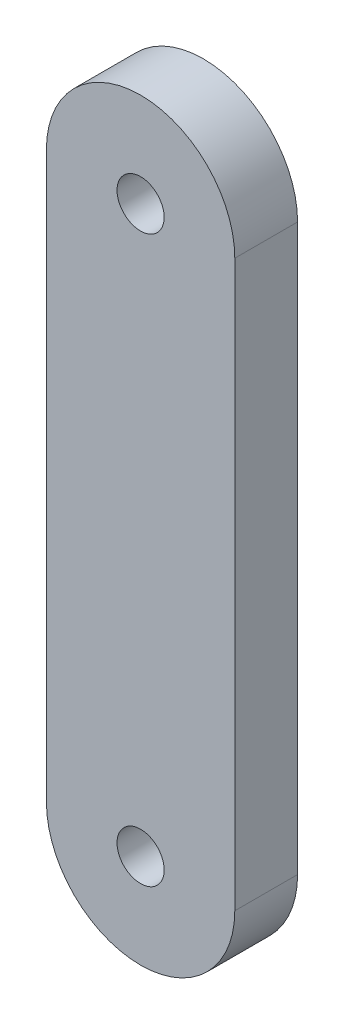
SolidWorks part; units mm, degrees
ref_plane "前视基准面" through (0, 0, 0) normal (0, 0, 1) x (1, 0, 0)
ref_plane "上视基准面" through (0, 0, 0) normal (0, 1, 0) x (1, 0, 0)
ref_plane "右视基准面" through (0, 0, 0) normal (1, 0, 0) x (0, 0, -1)
ref_plane "基准面4" through (0, 0, 8) normal (0, 0, 1) x (1, 0, 0)
sketch "草图1" plane through (0, 0, 8) normal (0, 0, 1) x (1, 0, 0)
  line L0 (12, -36) -> (12, 36)
  line L1 (-12, 36) -> (-12, -36)
  circle A0 centre (0, -36) radius 3
  circle A1 centre (0, 36) radius 3
  arc A5 (12, 36) -> (-12, 36) centre (0, 36) ccw
  arc A6 (-12, -36) -> (12, -36) centre (0, -36) ccw
  dimension "D1" = 6
  dimension "D2" = 6
extrude "凸台-拉伸1" add sketch "草图1" against normal blind 8
